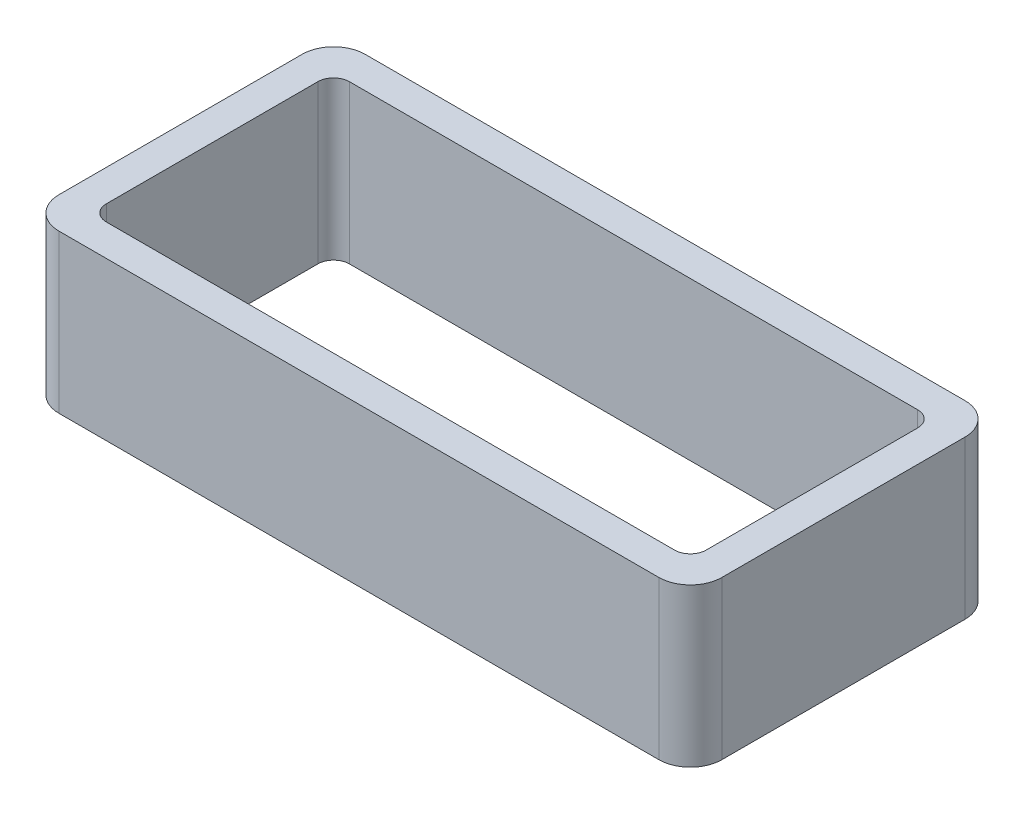
SolidWorks part; units mm, degrees
ref_plane "Спереди" through (0, 0, 0) normal (0, 0, 1) x (1, 0, 0)
ref_plane "Сверху" through (0, 0, 0) normal (0, 1, 0) x (1, 0, 0)
ref_plane "Справа" through (0, 0, 0) normal (1, 0, 0) x (0, 0, -1)
sketch "Эскиз1" plane through (0, 0, 0) normal (0, 1, 0) x (1, 0, 0)
  line L0 (-10.5, 3.85) -> (-10.5, -3.85)
  line L1 (-9, 3.85) -> (9, 3.85)
  line L2 (-9.5, 3.35) -> (-9.5, -3.35)
  line L3 (-9, -3.85) -> (9, -3.85)
  line L4 (9.5, 3.35) -> (9.5, -3.35)
  line L5 (-9.5, 3.85) -> (9.5, -3.85) construction
  line L6 (-9.5, -3.85) -> (9.5, 3.85) construction
  line L7 (-9.5, -4.85) -> (9.5, -4.85)
  line L8 (10.5, 3.85) -> (10.5, -3.85)
  line L9 (-9.5, 4.85) -> (9.5, 4.85)
  line L10 (-10.5, 4.85) -> (10.5, 4.85) construction
  line L11 (10.5, 4.85) -> (10.5, -4.85) construction
  line L12 (-10.5, -4.85) -> (10.5, -4.85) construction
  line L13 (-10.5, 4.85) -> (-10.5, -4.85) construction
  line L14 (-9.5, 3.85) -> (9.5, 3.85) construction
  line L15 (9.5, 3.85) -> (9.5, -3.85) construction
  line L16 (-9.5, -3.85) -> (9.5, -3.85) construction
  line L17 (-9.5, 3.85) -> (-9.5, -3.85) construction
  arc A0 (9.5, 4.85) -> (10.5, 3.85) centre (9.5, 3.85) cw
  arc A1 (10.5, -3.85) -> (9.5, -4.85) centre (9.5, -3.85) cw
  arc A2 (-9.5, -4.85) -> (-10.5, -3.85) centre (-9.5, -3.85) cw
  arc A3 (-10.5, 3.85) -> (-9.5, 4.85) centre (-9.5, 3.85) cw
  arc A4 (9, 3.85) -> (9.5, 3.35) centre (9, 3.35) cw
  arc A5 (9.5, -3.35) -> (9, -3.85) centre (9, -3.35) cw
  arc A6 (-9, -3.85) -> (-9.5, -3.35) centre (-9, -3.35) cw
  arc A7 (-9.5, 3.35) -> (-9, 3.85) centre (-9, 3.35) cw
  point P0 (0, 0)
  dimension "D4" = 1
  dimension "D5" = 0.5
  dimension "D1" = 19
  dimension "D2" = 7.7
  dimension "D3" = 1
extrude "Бобышка-Вытянуть1" add sketch "Эскиз1" along normal blind 5
